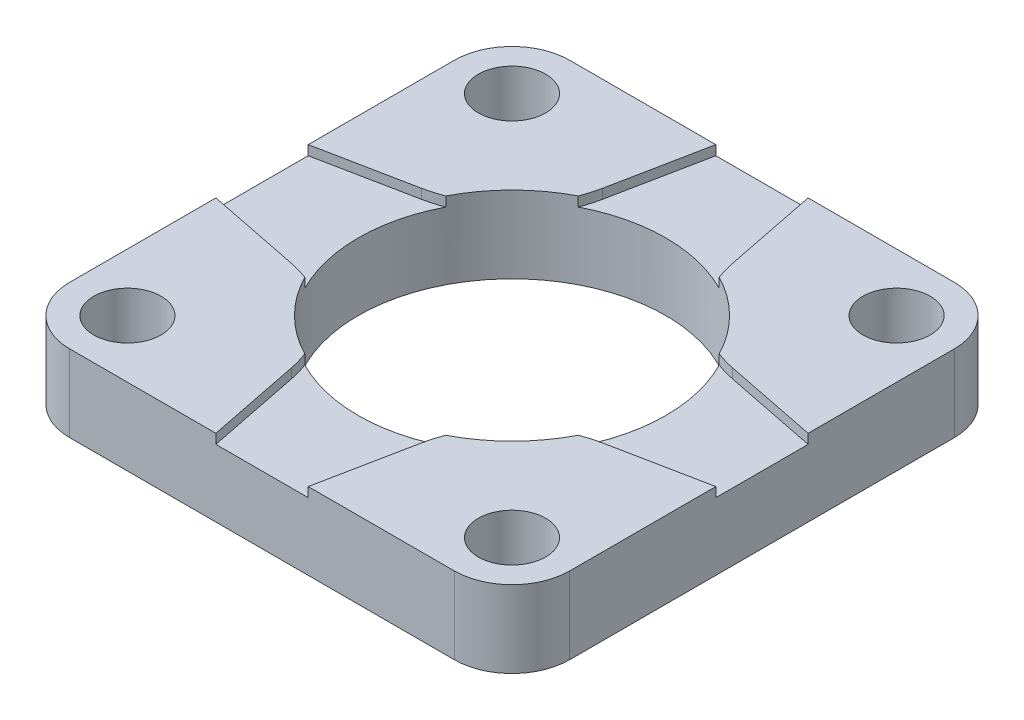
SolidWorks part; units mm, degrees
ref_plane "前视基准面" through (0, 0, 0) normal (0, 0, 1) x (1, 0, 0)
ref_plane "上视基准面" through (0, 0, 0) normal (0, 1, 0) x (1, 0, 0)
ref_plane "右视基准面" through (0, 0, 0) normal (1, 0, 0) x (0, 0, -1)
sketch "草图2" plane through (0, 0, 0) normal (0, 1, 0) x (1, 0, 0)
  line L0 (-13, 10) -> (-13, -10)
  line L1 (-7.0403, 10) -> (-7, 10)
  line L7 (-10, -13) -> (10, -13)
  line L8 (13, -10) -> (13, 10)
  line L10 (10, 13) -> (-10, 13)
  line L11 (-5.6569, 5.6569) -> (5.6569, -5.6569) construction
  line L13 (-5.6569, -5.6569) -> (5.6569, 5.6569) construction
  circle A1 centre (0, 0) radius 8
  arc A2 (-10, 13) -> (-13, 10) centre (-10, 10) ccw
  arc A3 (13, 10) -> (10, 13) centre (10, 10) ccw
  arc A4 (10, -13) -> (13, -10) centre (10, -10) ccw
  arc A5 (-13, -10) -> (-10, -13) centre (-10, -10) ccw
  circle A6 centre (-10, 10) radius 1.75
  circle A7 centre (10, 10) radius 1.75
  circle A8 centre (10, -10) radius 1.75
  circle A9 centre (-10, -10) radius 1.75
  point P0 (0, 0)
  point P19 (0, 0)
  point P35 (0, 0)
  dimension "D1" = 4
  dimension "D2" = 4
extrude "凸台-拉伸1" add sketch "草图2" along normal blind 4
sketch "草图3" plane through (0, 4, 0) normal (0, 1, 0) x (1, 0, 0)
  line L0 (0, 0) -> (5, 0)
  line L1 (0, 0) -> (0, -25)
  line L2 (0, -25) -> (3.3822, -8.089)
  line L3 (0, 0) -> (-5, 0)
  line L4 (-3.3822, -8.089) -> (0, -25)
  line L5 (8.089, -3.3822) -> (25, 0)
  line L6 (25, 0) -> (8.089, 3.3822)
  line L7 (0, 0) -> (0, 5)
  line L8 (3.3822, 8.089) -> (0, 25)
  line L9 (0, 25) -> (-3.3822, 8.089)
  line L10 (0, 0) -> (-5, 0)
  line L11 (-8.089, 3.3822) -> (-25, 0)
  line L12 (-25, 0) -> (-8.089, -3.3822)
  line L13 (0, 0) -> (0, -5)
  arc A0 (-8.089, -3.3822) -> (-3.3822, -8.089) centre (-9.2657, -9.2657) cw
  arc A1 (3.3822, -8.089) -> (8.089, -3.3822) centre (9.2657, -9.2657) cw
  arc A2 (8.089, 3.3822) -> (3.3822, 8.089) centre (9.2657, 9.2657) cw
  arc A3 (-3.3822, 8.089) -> (-8.089, 3.3822) centre (-9.2657, 9.2657) cw
  point P17 (0, 0)
  circle M5 centre (0, 0) radius 8
  line M6 (-13, 10) -> (-13, -10)
  line M8 (-10, -13) -> (10, -13)
  line M10 (13, -10) -> (13, 10)
  line M12 (10, 13) -> (-10, 13)
  dimension "D1" = 4
  dimension "D2" = 6
extrude "切除-拉伸1" cut sketch "草图3" against normal blind 0.5 contours A3 L11 L12 A0 M5 M6 | L9 A3 A2 L8 M5 M12 | L6 A2 A1 L5 M5 M10 | A0 L4 L1 M5 M8 | L2 A1 L1 M5 M8
